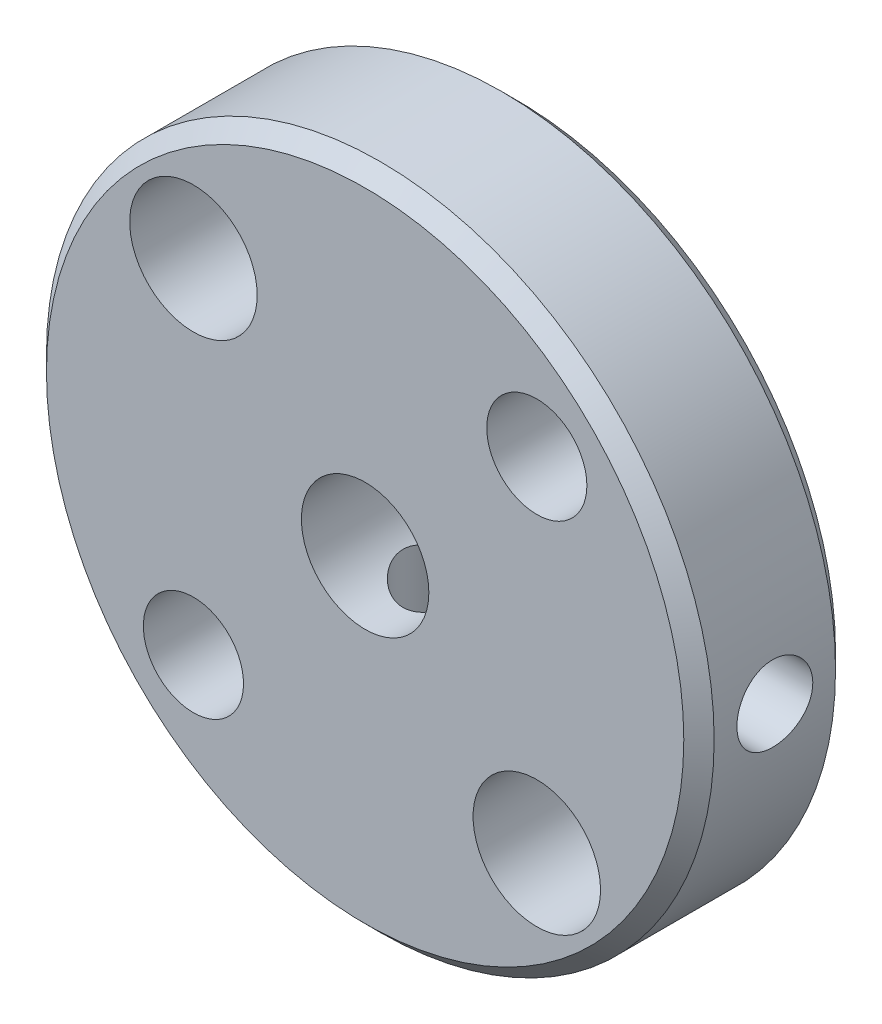
SolidWorks part; units mm, degrees
material "Alliage 2014"
ref_plane "Face" through (0, 0, 0) normal (0, 0, 1) x (1, 0, 0)
ref_plane "Dessus" through (0, 0, 0) normal (0, 1, 0) x (1, 0, 0)
ref_plane "Droite" through (0, 0, 0) normal (1, 0, 0) x (0, 0, -1)
sketch "Esquisse1" plane through (0, 0, 0) normal (0, 0, 1) x (1, 0, 0)
  circle A0 centre (0, 0) radius 4
  dimension "D1" = 8
extrude "Boss.-Extru.1" add sketch "Esquisse1" along normal blind 4
sketch "Esquisse2" plane through (0, 0, 4) normal (0, 0, 1) x (1, 0, 0)
  circle A0 centre (0, 0) radius 11
  dimension "D1" = 22
extrude "Boss.-Extru.2" add sketch "Esquisse2" along normal blind 5
sketch "Esquisse3" plane through (0, 0, 9) normal (0, 0, 1) x (1, 0, 0)
  line L0 (-7.7782, 7.7782) -> (7.7782, -7.7782) construction
  line L1 (11, 0) -> (-11, 0) construction
  circle A0 centre (0, 0) radius 8 construction
  circle A1 centre (0, 0) radius 11 construction
  circle A2 centre (-5.6569, 5.6569) radius 2.1
  circle A3 centre (5.6569, -5.6569) radius 2.1
  circle A4 centre (0, 0) radius 2.1
  dimension "D1" = 16
  dimension "D2" = 4.2
  dimension "D3" = 45
extrude "Enlèv. mat.-Extru.1" cut sketch "Esquisse3" against normal through all
hole_wizard "Trou taraudé M41" positions "Esquisse5" profile "Esquisse4" tap size "M4" standard "Iso" end condition through all
sketch "Esquisse5" plane through (0, 0, 9) normal (0, 0, 1) x (1, 0, 0)
  line L0 (7.7782, 7.7782) -> (-7.7782, -7.7782) construction
  line L1 (-7.7782, 7.7782) -> (7.7782, -7.7782) construction
  line L2 (-7.7782, 7.7782) -> (7.7782, -7.7782) construction
  circle A0 centre (0, 0) radius 8 construction
  circle A1 centre (0, 0) radius 11 construction
  point P13 (5.6569, 5.6569)
  point P15 (-5.6569, -5.6569)
sketch "Esquisse4" plane through (5.6569, 5.6569, 9) normal (1, 0, 0) x (0, -1, 0)
  line L0 (0, 0) -> (0, 9)
  line L1 (0, 9) -> (1.65, 9)
  line L2 (1.65, 9) -> (1.65, 0)
  line L5 (1.65, 0) -> (0, 0)
  line L11 (0, -6.35) -> (0, 107.95) construction
  dimension "Diamètre du trou pour taraudage jusqu'au prochain" = 3.3
  dimension "Profondeur du trou pour taraudage jusqu'au prochain" = 9
cosmetic thread "Filetage de perçage1" parameters "D2"=4
cosmetic thread "Filetage de perçage2" parameters "D2"=4
sketch "Esquisse6" plane through (0, 0, 0) normal (0, 1, 0) x (1, 0, 0)
  line L0 (-11, -9) -> (11, -9) construction
  line L1 (11, -4) -> (-11, -4) construction
  line L2 (-11, -9) -> (11, -9) construction
  line L3 (11, -4) -> (-11, -4) construction
  line L4 (0, -9) -> (0, -4) construction
  circle A0 centre (0, -6.5) radius 1.25
  dimension "D1" = 2.5
extrude "Enlèv. mat.-Extru.2" cut sketch "Esquisse6" against normal through all
cosmetic thread "Représentation de filetage1" parameters "D2"=3
pattern_circular "Répétition circulaire1" count 2 every 90 about axis through (0, 0, 9) along (0, 0, -1) of "Enlèv. mat.-Extru.2"
chamfer "Chanfrein1" distance 0.5 angle 45 3 edges at (11, 0, 9) (11, 0, 4) (4, 0, 0)
